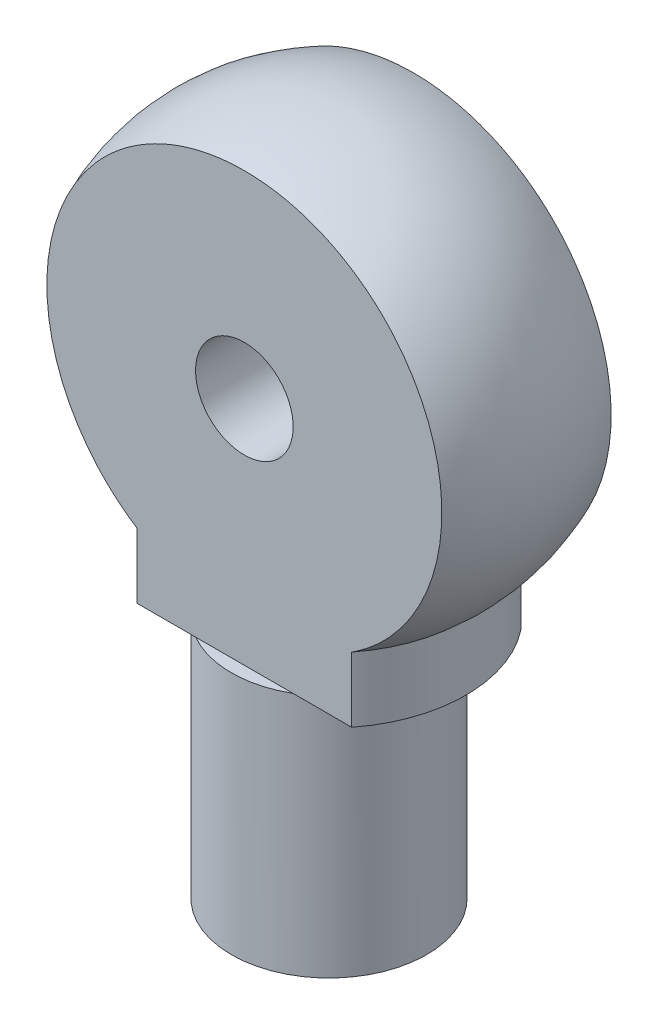
SolidWorks part; units mm, degrees
ref_plane "Front Plane" through (0, 0, 0) normal (0, 0, 1) x (1, 0, 0)
ref_plane "Top Plane" through (0, 0, 0) normal (0, 1, 0) x (1, 0, 0)
ref_plane "Right Plane" through (0, 0, 0) normal (1, 0, 0) x (0, 0, -1)
sketch "Sketch1" plane through (0, 0, 0) normal (0, 1, 0) x (1, 0, 0)
  circle A0 centre (0, 0) radius 7.62
extrude "Boss-Extrude1" add sketch "Sketch1" along normal blind 19.05
sketch "Sketch2" plane through (0, 0, 0) normal (1, 0, 0) x (0, 0, -1)
  line L0 (0, 8.382) -> (0, -8.382) construction
  line L1 (-10.668, 19.05) -> (-10.668, 24.13)
  line L2 (-10.668, 19.05) -> (0, 19.05)
  line L3 (7.62, 19.05) -> (-7.62, 19.05) construction
  line L4 (0, 19.05) -> (0, 53.8256)
  arc A0 (0, 53.8256) -> (-10.668, 24.13) centre (0, 37.0616) ccw
  dimension "D3" = 33.528
  dimension "D1" = 5.08
  dimension "D2" = 10.668
revolve "Revolve1" add sketch "Sketch2" angle 360 about L4
sketch "Sketch3" plane through (0, 0, 0) normal (1, 0, 0) x (0, 0, -1)
  line L0 (-7.62, 19.05) -> (7.62, 19.05) construction
  line L1 (-6.604, 19.05) -> (-28.2389, 19.05)
  line L2 (-6.604, 19.05) -> (-6.604, 63.5882)
  line L3 (-6.604, 63.5882) -> (-28.2389, 63.5882)
  line L4 (-28.2389, 19.05) -> (-28.2389, 63.5882)
  line L5 (0, 18.4404) -> (0, -18.4404) construction
  line L6 (6.604, 19.05) -> (31.5571, 19.05)
  line L7 (6.604, 19.05) -> (6.604, 63.5882)
  line L8 (6.604, 63.5882) -> (31.5571, 63.5882)
  line L9 (31.5571, 19.05) -> (31.5571, 63.5882)
  dimension "D1" = 13.208
  dimension "D2" = 6.604
extrude "Cut-Extrude1" cut sketch "Sketch3" against normal through all both and the other way through all
sketch "Sketch4" plane through (0, 0, -6.604) normal (0, 0, -1) x (-1, 0, 0)
  circle A0 centre (0, 37.0616) radius 3.81
  arc A1 (8.3782, 24.13) -> (-8.3782, 24.13) centre (0, 37.0616) ccw construction
extrude "Cut-Extrude2" cut sketch "Sketch4" against normal through all both
sketch "Sketch6" plane through (0, 0, 6.604) normal (0, 0, 1) x (1, 0, 0)
  point P0 (0, 37.0616)
